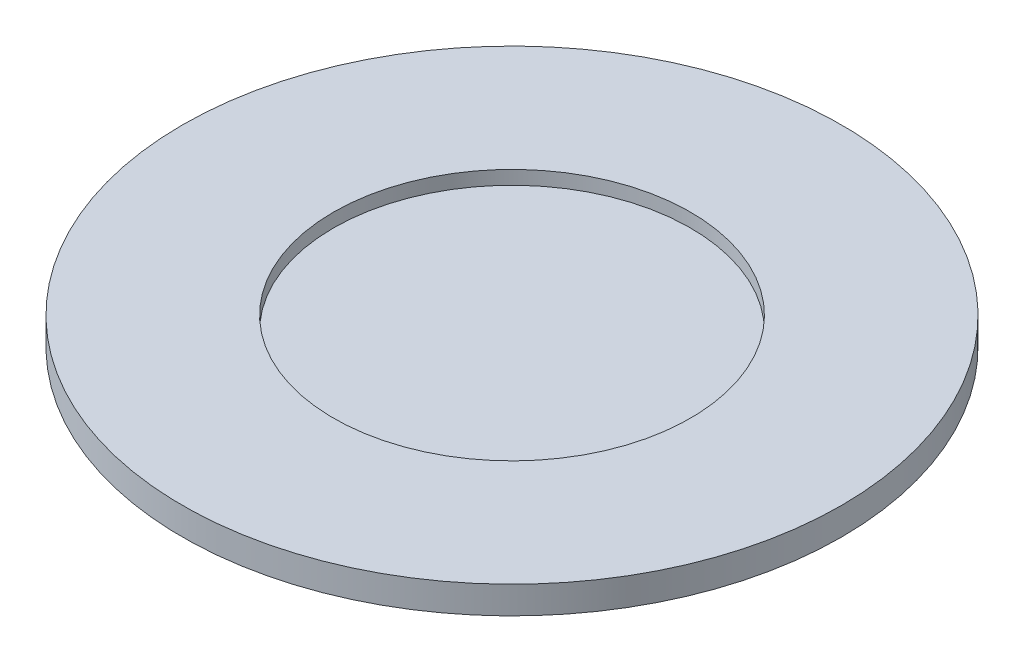
SolidWorks part; units mm, degrees
ref_plane "Plane1" through (0, 0, 0) normal (0, 0, 1) x (1, 0, 0)
ref_plane "Plane2" through (0, 0, 0) normal (0, 1, 0) x (1, 0, 0)
ref_plane "Plane3" through (0, 0, 0) normal (1, 0, 0) x (0, 0, -1)
sketch "Эскиз1" plane through (0, 0, 0) normal (0, 0, 1) x (1, 0, 0)
  line L0 (5, 76.3411) -> (60, 76.3411)
  line L1 (60, 76.3411) -> (60, 66.3411)
  line L2 (60, 66.3411) -> (15, 66.3411)
  line L3 (10, 61.3411) -> (10, 56.3411)
  line L4 (10, 56.3411) -> (0, 56.3411)
  line L5 (0, 71.3411) -> (0, 56.3411)
  line L7 (-60, 97.7316) -> (-60, 42.2282) construction
  line L8 (5, 76.3411) -> (5, 71.3411)
  line L9 (5, 71.3411) -> (0, 71.3411)
  arc A0 (15, 66.3411) -> (10, 61.3411) centre (15, 61.3411) ccw
  point P10 (10, 66.3411)
  dimension "D5" = 5
  dimension "D1" = 65
  dimension "D2" = 10
  dimension "D3" = 10
  dimension "D4" = 10
  dimension "D6" = 60
  dimension "D7" = 15
  dimension "D8" = 120
revolve "Основание-Повернуть" add sketch "Эскиз1" angle 360 about L7
sketch "Эскиз2" plane through (0, 76.3411, 0) normal (0, 1, 0) x (-1, 0, 0)
  circle A0 centre (60, 0) radius 100 construction
  circle A1 centre (60, 0) radius 120 construction
  circle A2 centre (148.3269, 46.8866) radius 8
  dimension "D1" = 16
  dimension "D2" = 100
extrude "Вырез-Вытянуть1" [suppressed] cut sketch "Эскиз2" against normal through all
pattern_circular "Круговой массив1" [suppressed] count 8 over 360 about axis through (-60, 97.7316, 0) along (0, -1, 0)
sketch "Sketch1" plane through (0, 0, 0) normal (0, 0, 1) x (1, 0, 0)
  line L0 (-60, 56.3411) -> (0, 56.3411)
  line L1 (-130, 56.3411) -> (10, 56.3411) construction
  line L2 (0, 56.3411) -> (0, 71.3411)
  line L3 (0, 71.3411) -> (-60, 71.3411)
  line L4 (-60, 66.3411) -> (-60, 76.3411) construction
  line L5 (-60, 56.3411) -> (-60, 71.3411) construction
  line L6 (-60, 71.3411) -> (-60, 56.3411)
revolve "Revolve1" add sketch "Sketch1" angle 360
